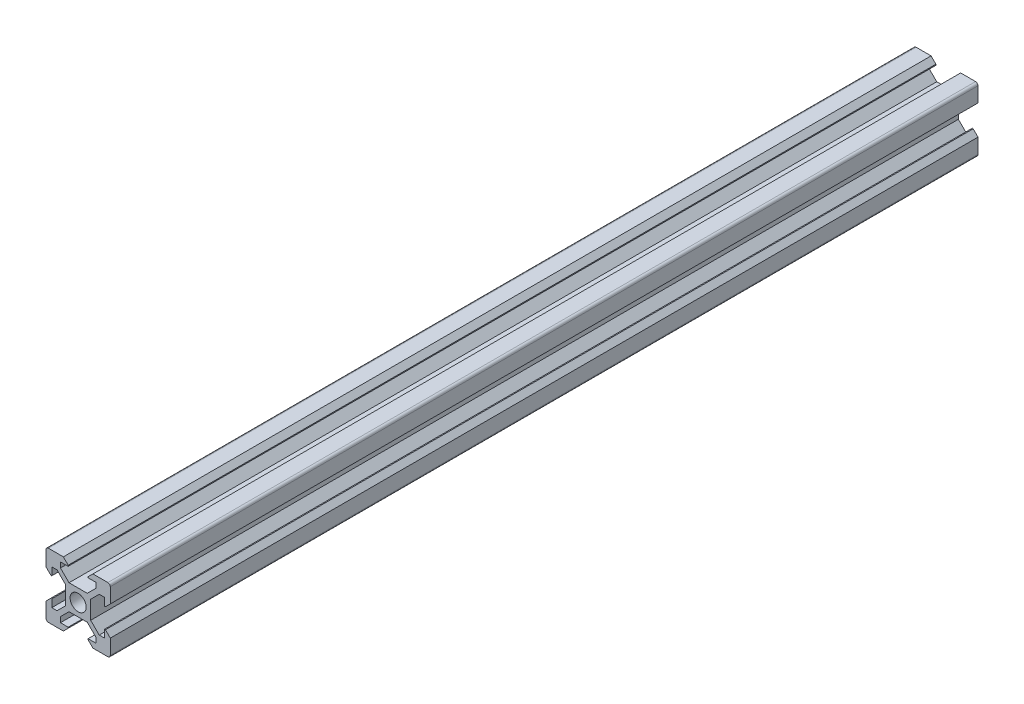
SolidWorks part; units mm, degrees
other "Markup1"
sketch "Sketch1" plane through (10, 10, 480) normal (0.5774, 0.5773, 0.5774) x (0.7071, 0, -0.7071)
ref_plane "Alzado" through (0, 0, 0) normal (0, 0, 1) x (1, 0, 0)
ref_plane "Planta" through (0, 0, 0) normal (0, 1, 0) x (1, 0, 0)
ref_plane "Vista lateral" through (0, 0, 0) normal (1, 0, 0) x (0, 0, -1)
sketch "Croquis1" plane through (0, 0, 0) normal (0, 0, 1) x (1, 0, 0)
  line L0 (-4.6, 10) -> (-3.1, 8.5)
  line L3 (-4.6, 10) -> (-9.25, 10)
  line L5 (-3.1, 8.5) -> (-3.1, 8.2)
  line L6 (-3.1, 8.2) -> (-5.5, 8.2)
  line L7 (-5.5, 8.2) -> (-5.5, 6.5607)
  line L8 (-5.5, 6.5607) -> (-2.84, 3.9007)
  line L9 (-2.84, 3.9007) -> (0, 3.9007)
  line L10 (0, 0) -> (-15.3499, 15.3499) construction
  line L11 (-3.9007, 2.84) -> (-3.9007, 0)
  line L12 (-6.5607, 5.5) -> (-3.9007, 2.84)
  line L13 (-8.2, 5.5) -> (-6.5607, 5.5)
  line L14 (-8.2, 3.1) -> (-8.2, 5.5)
  line L15 (-8.5, 3.1) -> (-8.2, 3.1)
  line L16 (-10, 4.6) -> (-10, 9.25)
  line L17 (-10, 4.6) -> (-8.5, 3.1)
  line L18 (10, 4.6) -> (8.5, 3.1)
  line L19 (10, 4.6) -> (10, 9.25)
  line L20 (8.5, 3.1) -> (8.2, 3.1)
  line L21 (8.2, 3.1) -> (8.2, 5.5)
  line L22 (8.2, 5.5) -> (6.5607, 5.5)
  line L23 (6.5607, 5.5) -> (3.9007, 2.84)
  line L24 (3.9007, 2.84) -> (3.9007, 0)
  line L25 (5.5, 6.5607) -> (2.84, 3.9007)
  line L26 (5.5, 8.2) -> (5.5, 6.5607)
  line L27 (3.1, 8.2) -> (5.5, 8.2)
  line L28 (3.1, 8.5) -> (3.1, 8.2)
  line L29 (4.6, 10) -> (9.25, 10)
  line L30 (4.6, 10) -> (3.1, 8.5)
  line L31 (2.84, 3.9007) -> (0, 3.9007)
  line L32 (4.6, -10) -> (3.1, -8.5)
  line L33 (4.6, -10) -> (9.25, -10)
  line L34 (3.1, -8.5) -> (3.1, -8.2)
  line L35 (3.1, -8.2) -> (5.5, -8.2)
  line L36 (5.5, -8.2) -> (5.5, -6.5607)
  line L37 (5.5, -6.5607) -> (2.84, -3.9007)
  line L38 (2.84, -3.9007) -> (0, -3.9007)
  line L39 (6.5607, -5.5) -> (3.9007, -2.84)
  line L40 (8.2, -5.5) -> (6.5607, -5.5)
  line L41 (8.2, -3.1) -> (8.2, -5.5)
  line L42 (8.5, -3.1) -> (8.2, -3.1)
  line L43 (10, -4.6) -> (10, -9.25)
  line L44 (10, -4.6) -> (8.5, -3.1)
  line L45 (3.9007, -2.84) -> (3.9007, 0)
  line L46 (-10, -4.6) -> (-8.5, -3.1)
  line L47 (-10, -4.6) -> (-10, -9.25)
  line L48 (-8.5, -3.1) -> (-8.2, -3.1)
  line L49 (-8.2, -3.1) -> (-8.2, -5.5)
  line L50 (-8.2, -5.5) -> (-6.5607, -5.5)
  line L51 (-6.5607, -5.5) -> (-3.9007, -2.84)
  line L52 (-3.9007, -2.84) -> (-3.9007, 0)
  line L53 (-5.5, -6.5607) -> (-2.84, -3.9007)
  line L54 (-5.5, -8.2) -> (-5.5, -6.5607)
  line L55 (-3.1, -8.2) -> (-5.5, -8.2)
  line L56 (-3.1, -8.5) -> (-3.1, -8.2)
  line L57 (-4.6, -10) -> (-9.25, -10)
  line L58 (-4.6, -10) -> (-3.1, -8.5)
  line L59 (-2.84, -3.9007) -> (0, -3.9007)
  circle A0 centre (0, 0) radius 2.5
  arc A1 (-9.25, 10) -> (-10, 9.25) centre (-9.25, 9.25) ccw
  arc A2 (10, 9.25) -> (9.25, 10) centre (9.25, 9.25) ccw
  arc A3 (9.25, -10) -> (10, -9.25) centre (9.25, -9.25) ccw
  arc A4 (-10, -9.25) -> (-9.25, -10) centre (-9.25, -9.25) ccw
  point P18 (-10, 10)
  point P37 (10, 10)
  point P55 (10, -10)
  point P73 (-10, -10)
  point P79 (0, 0)
  dimension "D1" = 5
  dimension "D5" = 0.75
  dimension "D2" = 10
  dimension "D3" = 10
  dimension "D4" = 4.6
  dimension "D6" = 5.5
  dimension "D7" = 135
  dimension "D8" = 0.75
  dimension "D9" = 225
  dimension "D10" = 2.84
  dimension "D11" = 1.8
  dimension "D12" = 3.1
  dimension "D13" = 4
extrude "Saliente-Extruir1" add sketch "Croquis1" along normal blind 350
sketch "Sketch2" plane through (0, 0, 0) normal (0, 1, 0) x (1, 0, 0)
  line L0 (-4.6, 0) -> (-9.25, 0) construction
  line L1 (-57.4359, -270) -> (82.1467, -270)
  line L2 (-57.4359, -270) -> (-57.4359, -512.4329)
  line L3 (-57.4359, -512.4329) -> (82.1467, -512.4329)
  line L4 (82.1467, -270) -> (82.1467, -512.4329)
  dimension "D1" = 270
extrude "Cut-Extrude1" cut sketch "Sketch2" against normal blind 40 and the other way blind 47
